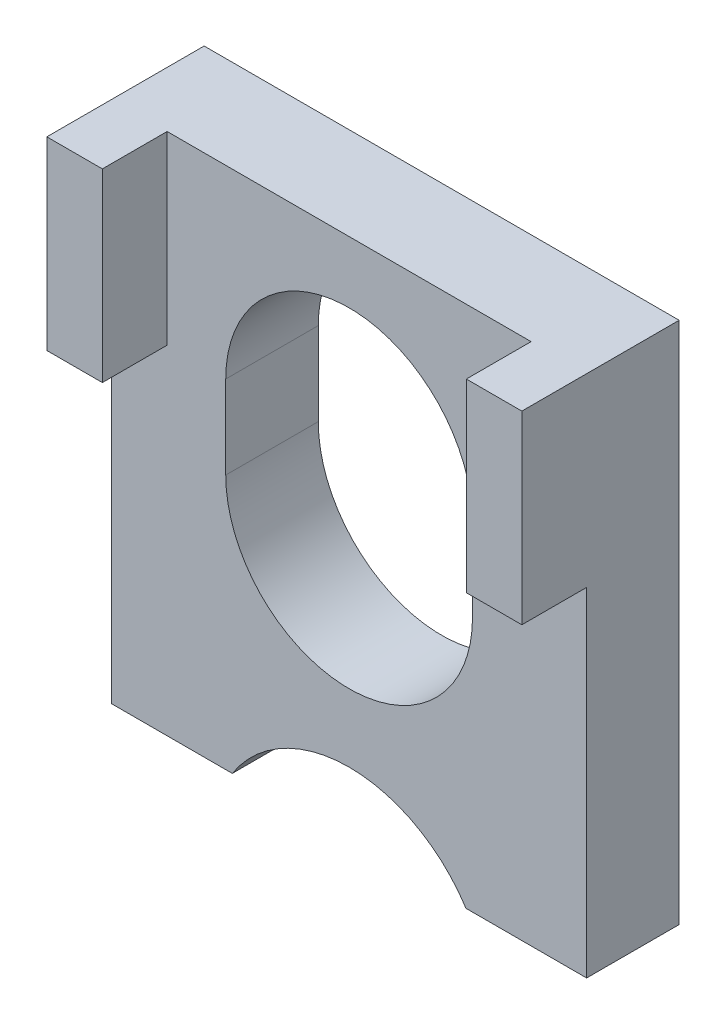
SolidWorks part; units mm, degrees
ref_plane "Спереди" through (0, 0, 0) normal (0, 0, 1) x (1, 0, 0)
ref_plane "Сверху" through (0, 0, 0) normal (0, 1, 0) x (1, 0, 0)
ref_plane "Справа" through (0, 0, 0) normal (1, 0, 0) x (0, 0, -1)
sketch "Эскиз1" plane through (0, 0, 0) normal (0, 0, 1) x (1, 0, 0)
  line L1 (-7.7, 13.7375) -> (7.7, 13.7375)
  line L5 (-7.7, 13.7375) -> (-7.7, -0.0396)
  line L6 (7.7, 13.7375) -> (7.7, -0.0396)
  line L7 (-7.7, -0.0396) -> (-7.7, -3.2297)
  line L8 (-7.7, -3.2297) -> (-3.788, -3.2297)
  line L9 (0, 7.7375) -> (0, 5.041) construction
  line L10 (4, 7.7375) -> (4, 5.041)
  line L11 (-4, 7.7375) -> (-4, 5.041)
  line L12 (7.7, -0.0396) -> (7.7, -3.2297)
  line L13 (7.7, -3.2297) -> (3.788, -3.2297)
  arc A0 (-3.788, -3.2297) -> (3.788, -3.2297) centre (0, -5.659) cw
  arc A1 (4, 7.7375) -> (-4, 7.7375) centre (0, 7.7375) ccw
  arc A2 (-4, 5.041) -> (4, 5.041) centre (0, 5.041) ccw
  point P1 (0, 6.3893)
  point P15 (0, 11.7375)
  point P16 (0, 1.041)
  dimension "D1" = 4.5
  dimension "D5" = 4
  dimension "D4" = 2.2
  dimension "D2" = 15.4
  dimension "D3" = 7.7
  dimension "D6" = 10.6965
  dimension "D7" = 2
  dimension "D8" = 7.7
extrude "Бобышка-Вытянуть1" add sketch "Эскиз1" along normal blind 3
sketch "Эскиз2" plane through (0, 0, 3) normal (0, 0, 1) x (1, 0, 0)
  line L1 (-7.7, 13.7375) -> (-5.9, 13.7375)
  line L2 (-7.7, 13.7375) -> (-7.7, 7.7375)
  line L3 (-7.7, 7.7375) -> (-5.9, 7.7375)
  line L4 (-5.9, 13.7375) -> (-5.9, 7.7375)
  line L5 (7.7, 13.7375) -> (5.9, 13.7375)
  line L6 (7.7, 13.7375) -> (7.7, 7.7375)
  line L7 (7.7, 7.7375) -> (5.9, 7.7375)
  line L8 (5.9, 13.7375) -> (5.9, 7.7375)
  dimension "D1" = 1.8
  dimension "D2" = 1.8
  dimension "D3" = 6
  dimension "D4" = 6
extrude "Бобышка-Вытянуть2" add sketch "Эскиз2" along normal blind 2.1
